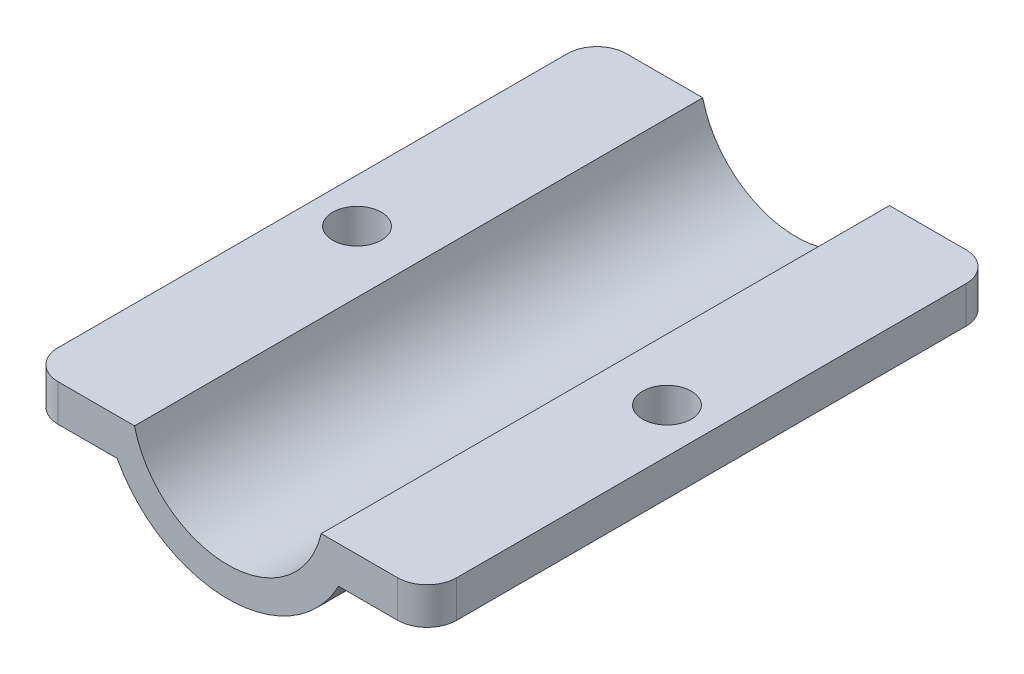
SolidWorks part; units mm, degrees
material "打印件"
ref_plane "前视基准面" through (0, 0, 0) normal (0, 0, 1) x (1, 0, 0)
ref_plane "上视基准面" through (0, 0, 0) normal (0, 1, 0) x (1, 0, 0)
ref_plane "右视基准面" through (0, 0, 0) normal (1, 0, 0) x (0, 0, -1)
sketch "草图1" plane through (0, 0, 0) normal (0, 0, 1) x (1, 0, 0)
  line L0 (-6.3246, -1.5) -> (-13.5, -1.5)
  line L1 (-13.5, -1.5) -> (-13.5, -4)
  line L2 (-13.5, -4) -> (-7.5, -4)
  line L3 (6.3246, -1.5) -> (13.5, -1.5)
  line L4 (13.5, -1.5) -> (13.5, -4)
  line L5 (13.5, -4) -> (7.5, -4)
  arc A0 (-6.3246, -1.5) -> (6.3246, -1.5) centre (0, 0) ccw
  arc A1 (-7.5, -4) -> (7.5, -4) centre (0, 0) ccw
  dimension "D1" = 6.5
  dimension "D2" = 8.5
  dimension "D3" = 2.5
  dimension "D4" = 6
  dimension "D5" = 1.5
extrude "凸台-拉伸1" add sketch "草图1" along normal blind 38.5
sketch "草图2" plane through (0, -4, 0) normal (0, -1, 0) x (1, 0, 0)
  line L0 (-10.5, 38.5) -> (-10.5, 0) construction
  line L1 (-13.5, 38.5) -> (-7.5, 38.5) construction
  line L2 (-13.5, 0) -> (-7.5, 0) construction
  line L3 (10.5, 38.5) -> (10.5, 0) construction
  line L4 (7.5, 38.5) -> (13.5, 38.5) construction
  line L5 (7.5, 0) -> (13.5, 0) construction
  circle A0 centre (-10.5, 19.25) radius 1.65
  circle A1 centre (10.5, 19.25) radius 1.65
  dimension "D1" = 3.3
extrude "切除-拉伸1" cut sketch "草图2" against normal through all
fillet "圆角1" radius 2 4 edges at (13.5, -2.75, 38.5) (-13.5, -2.75, 38.5) (13.5, -2.75, 0) (-13.5, -2.75, 0)
